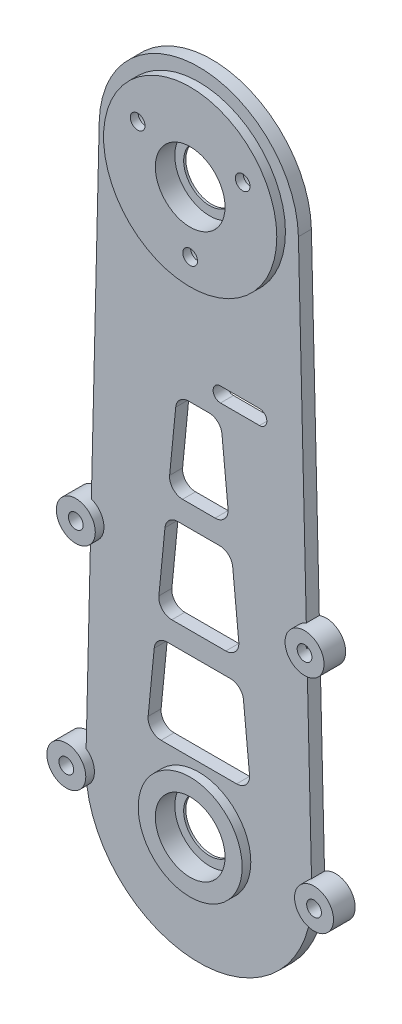
SolidWorks part; units mm, degrees
ref_plane "Front Plane" through (0, 0, 0) normal (0, 0, 1) x (1, 0, 0)
ref_plane "Top Plane" through (0, 0, 0) normal (0, 1, 0) x (1, 0, 0)
ref_plane "Right Plane" through (0, 0, 0) normal (1, 0, 0) x (0, 0, -1)
ref_plane "Plane1" through (0, 0, 328.5) normal (0, 0, 1) x (1, 0, 0)
sketch "Sketch1" plane through (0, 0, 328.5) normal (0, 0, 1) x (1, 0, 0)
  line L0 (277.0065, 300.5482) -> (273.9088, 170.6221)
  line L1 (326.0912, 170.6221) -> (322.9935, 300.5482)
  line L2 (305, 258.3) -> (314, 258.3)
  line L3 (314, 261.7) -> (305, 261.7)
  line L4 (294.6613, 252.2924) -> (293.2574, 237.9591)
  line L5 (296.2431, 234.6667) -> (303.7569, 234.6667)
  line L6 (306.7426, 237.9591) -> (305.3387, 252.2924)
  line L7 (302.353, 255) -> (297.647, 255)
  line L8 (292.1801, 226.9591) -> (290.7762, 212.6258)
  line L9 (293.762, 209.3333) -> (306.238, 209.3333)
  line L10 (309.2238, 212.6258) -> (307.8199, 226.9591)
  line L11 (304.8342, 229.6667) -> (295.1658, 229.6667)
  line L12 (289.6989, 201.6258) -> (288.2951, 187.2924)
  line L13 (291.2808, 184) -> (308.7192, 184)
  line L14 (311.7049, 187.2924) -> (310.3011, 201.6258)
  line L15 (307.3154, 204.3333) -> (292.6846, 204.3333)
  arc A0 (273.9088, 170.6221) -> (326.0912, 170.6221) centre (300, 170) ccw
  arc A1 (322.9935, 300.5482) -> (277.0065, 300.5482) centre (300, 300) ccw
  circle A2 centre (300, 300) radius 6
  circle A3 centre (300, 170) radius 6
  arc A4 (314, 258.3) -> (314, 261.7) centre (314, 260) ccw
  arc A5 (305, 261.7) -> (305, 258.3) centre (305, 260) ccw
  circle A6 centre (312.1244, 307) radius 1.7
  circle A7 centre (287.8756, 307) radius 1.7
  circle A8 centre (300, 286) radius 1.7
  arc A9 (297.647, 255) -> (294.6613, 252.2924) centre (297.647, 252) ccw
  arc A10 (293.2574, 237.9591) -> (296.2431, 234.6667) centre (296.2431, 237.6667) ccw
  arc A11 (303.7569, 234.6667) -> (306.7426, 237.9591) centre (303.7569, 237.6667) ccw
  arc A12 (305.3387, 252.2924) -> (302.353, 255) centre (302.353, 252) ccw
  arc A13 (295.1658, 229.6667) -> (292.1801, 226.9591) centre (295.1658, 226.6667) ccw
  arc A14 (290.7762, 212.6258) -> (293.762, 209.3333) centre (293.762, 212.3333) ccw
  arc A15 (306.238, 209.3333) -> (309.2238, 212.6258) centre (306.238, 212.3333) ccw
  arc A16 (307.8199, 226.9591) -> (304.8342, 229.6667) centre (304.8342, 226.6667) ccw
  arc A17 (292.6846, 204.3333) -> (289.6989, 201.6258) centre (292.6846, 201.3333) ccw
  arc A18 (288.2951, 187.2924) -> (291.2808, 184) centre (291.2808, 187) ccw
  arc A19 (308.7192, 184) -> (311.7049, 187.2924) centre (308.7192, 187) ccw
  arc A20 (310.3011, 201.6258) -> (307.3154, 204.3333) centre (307.3154, 201.3333) ccw
extrude "Boss-Extrude1" add sketch "Sketch1" along normal blind 3
ref_plane "Plane2" through (0, 0, 331.5) normal (0, 0, 1) x (1, 0, 0)
sketch "Sketch2" plane through (0, 0, 331.5) normal (0, 0, 1) x (1, 0, 0)
  circle A0 centre (300, 300) radius 20
  circle A1 centre (300, 300) radius 6
  circle A2 centre (312.1244, 307) radius 1.7
  circle A3 centre (287.8756, 307) radius 1.7
  circle A4 centre (300, 286) radius 1.7
extrude "Boss-Extrude2" add sketch "Sketch2" along normal blind 2
sketch "Sketch3" plane through (0, 0, 331.5) normal (0, 0, 1) x (1, 0, 0)
  circle A0 centre (300, 170) radius 12
  circle A1 centre (300, 170) radius 6
extrude "Boss-Extrude3" add sketch "Sketch3" along normal blind 2
sketch "Sketch4" plane through (0, 0, 328.5) normal (0, 0, 1) x (1, 0, 0)
  circle A0 centre (273.5932, 220) radius 4.5
  circle A1 centre (273.5932, 220) radius 1.7
extrude "Boss-Extrude4" add sketch "Sketch4" along normal blind 5
sketch "Sketch5" plane through (0, 0, 328.5) normal (0, 0, 1) x (1, 0, 0)
  circle A0 centre (326.4068, 220) radius 4.5
  circle A1 centre (326.4068, 220) radius 1.7
extrude "Boss-Extrude5" add sketch "Sketch5" along normal blind 5
sketch "Sketch6" plane through (0, 0, 328.5) normal (0, 0, 1) x (1, 0, 0)
  circle A0 centre (271.4014, 170) radius 4.5
  circle A1 centre (271.4014, 170) radius 1.7
extrude "Boss-Extrude6" add sketch "Sketch6" along normal blind 5
sketch "Sketch7" plane through (0, 0, 328.5) normal (0, 0, 1) x (1, 0, 0)
  circle A0 centre (328.5986, 170) radius 4.5
  circle A1 centre (328.5986, 170) radius 1.7
extrude "Boss-Extrude7" add sketch "Sketch7" along normal blind 5
ref_plane "Plane3" through (0, 0, 329) normal (0, 0, 1) x (1, 0, 0)
sketch "Sketch8" plane through (0, 0, 329) normal (0, 0, 1) x (1, 0, 0)
  circle A0 centre (300, 300) radius 8.05
  circle A1 centre (300, 170) radius 8.05
extrude "Cut-Extrude1" cut sketch "Sketch8" along normal blind 4.5
sketch "Sketch9" plane through (0, 0, 328.5) normal (0, 0, 1) x (1, 0, 0)
  circle A0 centre (312.1244, 307) radius 3.2
  circle A1 centre (287.8756, 307) radius 3.2
  circle A2 centre (300, 286) radius 3.2
extrude "Cut-Extrude2" cut sketch "Sketch9" along normal blind 3.2
